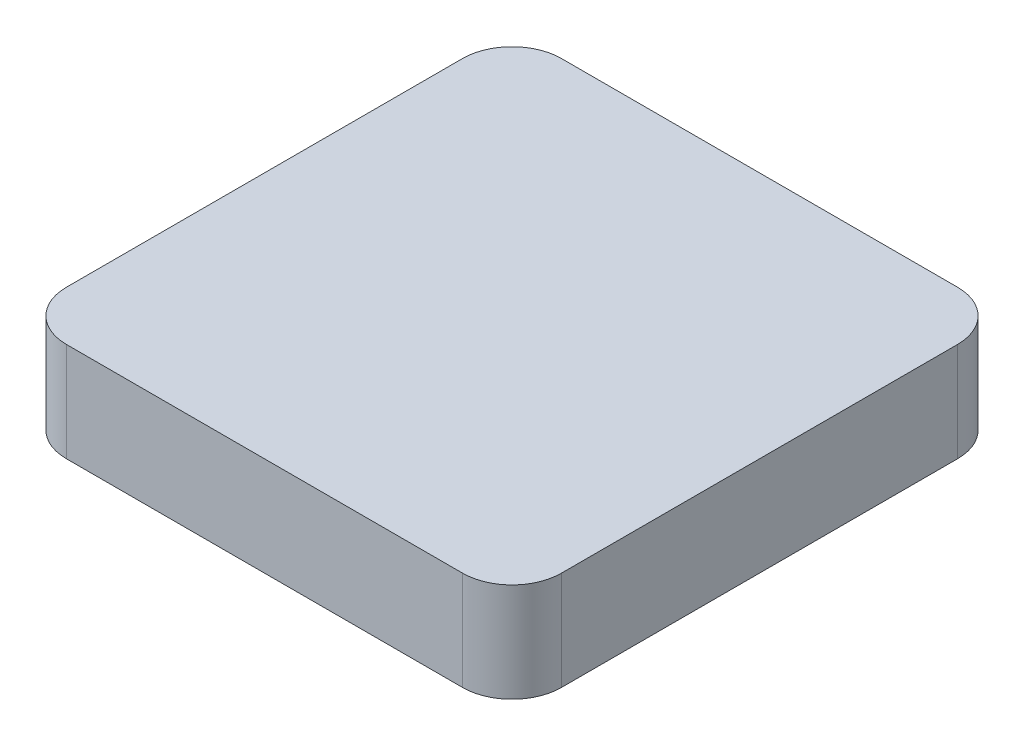
SolidWorks part; units mm, degrees
ref_plane "Front Plane" through (0, 0, 0) normal (0, 0, 1) x (1, 0, 0)
ref_plane "Top Plane" through (0, 0, 0) normal (0, 1, 0) x (1, 0, 0)
ref_plane "Right Plane" through (0, 0, 0) normal (1, 0, 0) x (0, 0, -1)
sketch "Sketch1" plane through (0, 0, 0) normal (0, 1, 0) x (1, 0, 0)
  line L1 (-50, -50) -> (50, -50)
  line L2 (-50, -50) -> (-50, 50)
  line L3 (-50, 50) -> (50, 50)
  line L4 (50, -50) -> (50, 50)
  line L5 (-50, -50) -> (50, 50) construction
  line L6 (-50, 50) -> (50, -50) construction
  point P0 (0, 0)
  dimension "D1" = 100
extrude "Boss-Extrude1" add sketch "Sketch1" along normal blind 20 contours L3 L4 L1 L2
fillet "Fillet1" radius 10 4 edges at (-50, 10, -50) (50, 10, -50) (50, 10, 50) (-50, 10, 50)
sketch "Sketch2" plane through (0, 20, 0) normal (0, 1, 0) x (1, 0, 0)
  point P0 (0, 0)
  point P1 (0, 0)
  point P3 (0, 0)
  point P4 (0, 0)
